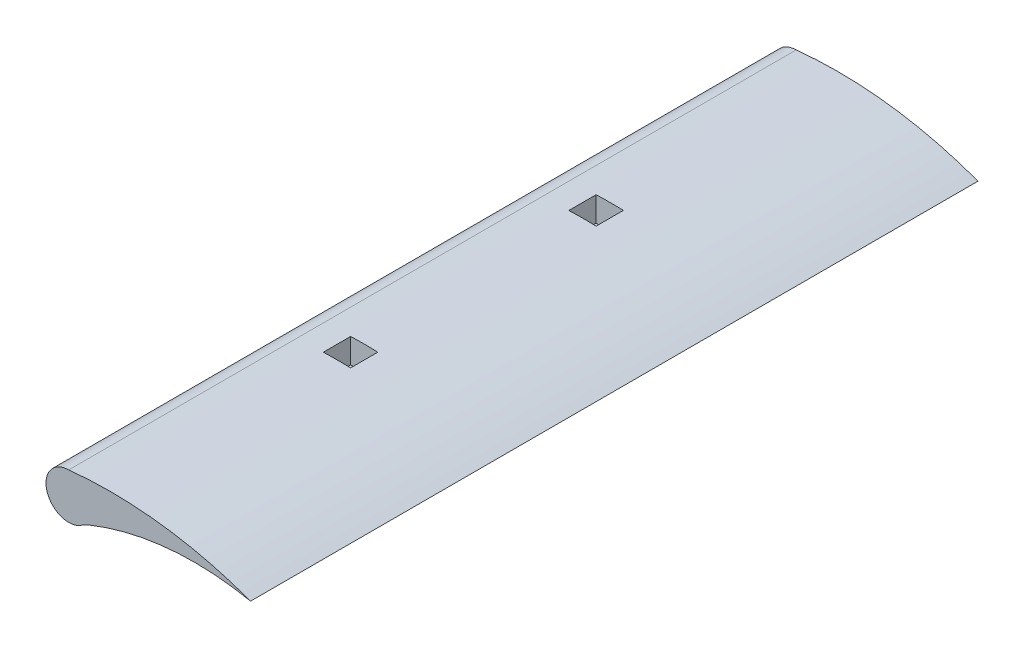
SolidWorks part; units mm, degrees
ref_plane "Front Plane" through (0, 0, 0) normal (0, 0, 1) x (1, 0, 0)
ref_plane "Top Plane" through (0, 0, 0) normal (0, 1, 0) x (1, 0, 0)
ref_plane "Right Plane" through (0, 0, 0) normal (1, 0, 0) x (0, 0, -1)
sketch "Sketch1" plane through (0, 0, 0) normal (0, 0, 1) x (1, 0, 0)
  arc A4 (0, 2.5) -> (1.3906, -2.0776) centre (0, 0) ccw
  arc A5 (0, 2.5) -> (20, 0) centre (4.6083, -41.8839) cw
  arc A6 (20, 0) -> (2.2268, -1.6346) centre (13.8252, -30.3032) ccw
  arc A7 (2.2268, -1.6346) -> (1.3906, -2.0776) centre (3.9577, -5.9128) ccw
  point P4 (0, 0)
extrude "Boss-Extrude2" add sketch "Sketch1" along normal mid plane 80
sketch "Sketch3" plane through (0, 0, 0) normal (0, 1, 0) x (1, 0, 0)
  line L0 (3, -15) -> (3, -12)
  line L1 (3, -12) -> (6, -12)
  line L2 (3, 15) -> (6, 15)
  line L3 (6, -12) -> (6, -15)
  line L4 (6, -15) -> (3, -15)
  line L5 (3, 15) -> (3, 12)
  line L6 (3, 12) -> (6, 12)
  line L7 (6, 15) -> (6, 12)
extrude "Cut-Extrude2" cut sketch "Sketch3" along normal through all
